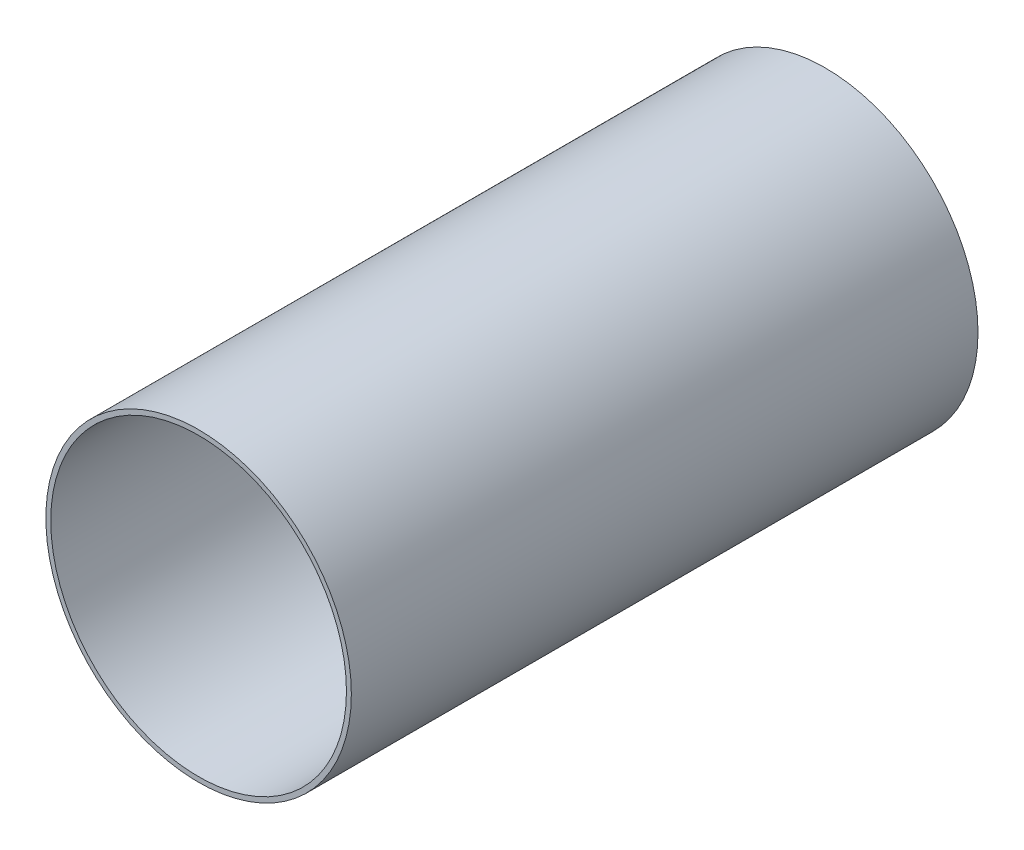
SolidWorks part; units mm, degrees
material "Thornel Mat VMA"
ref_plane "Front Plane" through (0, 0, 0) normal (0, 0, 1) x (1, 0, 0)
ref_plane "Top Plane" through (0, 0, 0) normal (0, 1, 0) x (1, 0, 0)
ref_plane "Right Plane" through (0, 0, 0) normal (1, 0, 0) x (0, 0, -1)
sketch "Sketch1" plane through (0, 0, 0) normal (0, 0, 1) x (1, 0, 0)
  circle A0 centre (0, 0) radius 49.53
  circle A1 centre (0, 0) radius 47.9425
  dimension "D1" = 99.06
  dimension "D2" = 1.5875
extrude "Boss-Extrude1" add sketch "Sketch1" along normal blind 203.2
